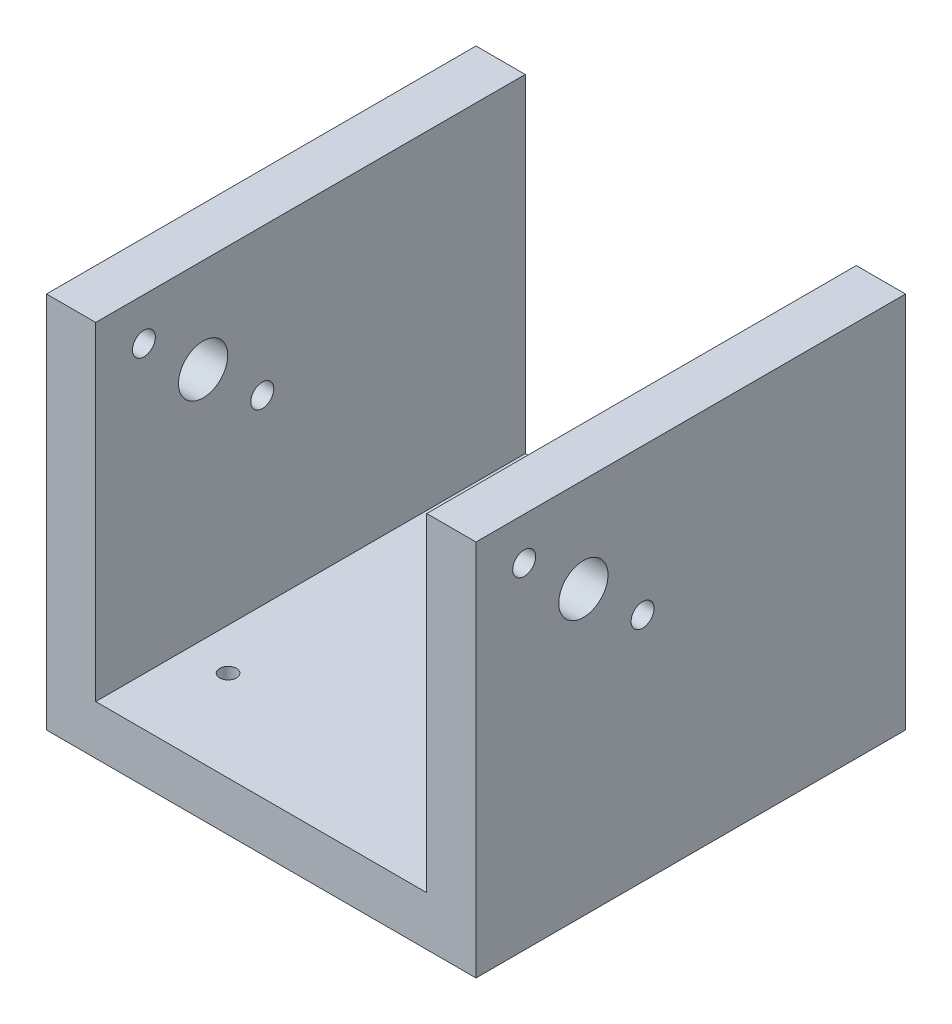
SolidWorks part; units mm, degrees
ref_plane "Front Plane" through (0, 0, 0) normal (0, 0, 1) x (1, 0, 0)
ref_plane "Top Plane" through (0, 0, 0) normal (0, 1, 0) x (1, 0, 0)
ref_plane "Right Plane" through (0, 0, 0) normal (1, 0, 0) x (0, 0, -1)
sketch "Sketch1" plane through (0, 0, 0) normal (0, 1, 0) x (1, 0, 0)
  line L0 (-65.4074, 35.4074) -> (-65.4074, 65.4074)
  line L1 (-37.7595, 37.7595) -> (37.7595, 37.7595) construction
  line L2 (-37.7595, 37.7595) -> (-37.7595, -37.7595) construction
  line L3 (-37.7595, -37.7595) -> (37.7595, -37.7595) construction
  line L4 (37.7595, 37.7595) -> (37.7595, -37.7595) construction
  line L5 (-37.7595, 37.7595) -> (37.7595, -37.7595) construction
  line L6 (-37.7595, -37.7595) -> (37.7595, 37.7595) construction
  line L7 (-35.4074, 65.4074) -> (35.4074, 65.4074)
  line L8 (-65.4074, 35.4074) -> (-65.4074, -35.4074)
  line L9 (-35.4074, -65.4074) -> (35.4074, -65.4074)
  line L10 (65.4074, 35.4074) -> (65.4074, -35.4074)
  line L11 (-65.4074, 65.4074) -> (65.4074, -65.4074) construction
  line L12 (-65.4074, -65.4074) -> (65.4074, 65.4074) construction
  line L13 (-65.4074, 65.4074) -> (-35.4074, 65.4074)
  line L14 (35.4074, 65.4074) -> (65.4074, 65.4074)
  line L15 (65.4074, 65.4074) -> (65.4074, 35.4074)
  line L16 (65.4074, -35.4074) -> (65.4074, -65.4074)
  line L17 (65.4074, -65.4074) -> (35.4074, -65.4074)
  line L18 (-65.4074, -35.4074) -> (-65.4074, -65.4074)
  line L19 (-65.4074, -65.4074) -> (-35.4074, -65.4074)
  circle A0 centre (37.7595, 37.7595) radius 2.55
  circle A1 centre (37.7595, -37.7595) radius 2.55
  circle A2 centre (-37.7595, -37.7595) radius 2.55
  circle A3 centre (-37.7595, 37.7595) radius 2.55
  arc A5 (-35.4074, -65.4074) -> (-65.4074, -35.4074) centre (-35.4074, -35.4074) cw construction
  arc A6 (-35.4074, 65.4074) -> (-65.4074, 35.4074) centre (-35.4074, 35.4074) ccw construction
  arc A7 (35.4074, 65.4074) -> (65.4074, 35.4074) centre (35.4074, 35.4074) cw construction
  arc A8 (65.4074, -35.4074) -> (35.4074, -65.4074) centre (35.4074, -35.4074) cw construction
  point P0 (0, 0)
  point P6 (0, 0)
  point P21 (0, 0)
  dimension "D3" = 5.1
  dimension "D5" = 30
  dimension "D1" = 106.8
  dimension "D2" = 185
  dimension "D4" = 4
extrude "Boss-Extrude1" add sketch "Sketch1" along normal blind 15
sketch "Sketch2" plane through (0, 15, 0) normal (0, 1, 0) x (1, 0, 0)
  line L4 (-65.4074, -65.4074) -> (65.4074, -65.4074)
  line L5 (65.4074, -65.4074) -> (65.4074, 65.4074)
  line L6 (65.4074, 65.4074) -> (-65.4074, 65.4074)
  line L7 (-65.4074, 65.4074) -> (-65.4074, -65.4074)
  line L9 (65.4074, -65.4074) -> (65.4074, 65.4074)
  line L11 (-65.4074, 65.4074) -> (-65.4074, -65.4074)
  line L21 (-50.4074, 50.4074) -> (-50.4074, -50.4074)
  line L23 (50.4074, -50.4074) -> (50.4074, 50.4074)
  line L24 (-65.4074, -65.4074) -> (65.4074, -65.4074)
  line L25 (65.4074, -65.4074) -> (65.4074, 65.4074)
  line L26 (65.4074, 65.4074) -> (-65.4074, 65.4074)
  line L27 (-65.4074, 65.4074) -> (-65.4074, -65.4074)
  line L28 (-65.4074, -65.4074) -> (-50.4074, -65.4074)
  line L29 (65.4074, -65.4074) -> (65.4074, 65.4074)
  line L30 (65.4074, 65.4074) -> (50.4074, 65.4074)
  line L31 (-65.4074, 65.4074) -> (-65.4074, -65.4074)
  line L32 (50.4074, 50.4074) -> (50.4074, 65.4074)
  line L33 (50.4074, -50.4074) -> (50.4074, -65.4074)
  line L34 (-50.4074, -50.4074) -> (-50.4074, -65.4074)
  line L35 (-50.4074, 50.4074) -> (-50.4074, 65.4074)
  line L36 (-50.4074, 65.4074) -> (-65.4074, 65.4074)
  line L37 (65.4074, 65.4074) -> (-65.4074, 65.4074) construction
  line L38 (50.4074, 50.4074) -> (-50.4074, 50.4074) construction
  line L39 (-50.4074, -50.4074) -> (50.4074, -50.4074) construction
  line L40 (50.4074, -65.4074) -> (65.4074, -65.4074)
  line L41 (-65.4074, -65.4074) -> (65.4074, -65.4074) construction
  line M18 (-65.4074, -65.4074) -> (65.4074, -65.4074)
  line M20 (65.4074, -65.4074) -> (65.4074, 65.4074)
  line M22 (65.4074, 65.4074) -> (-65.4074, 65.4074)
  line M24 (-65.4074, 65.4074) -> (-65.4074, -65.4074)
  dimension "D1" = 0
  dimension "D2" = 0
  dimension "D3" = 15
extrude "Boss-Extrude2" add sketch "Sketch2" along normal blind 100 contours L23 L33 L32 M18 M20 M22 | L21 L35 L34 M22 M24 M18
sketch "Sketch3" plane through (-65.4074, 0, 0) normal (-1, 0, 0) x (0, 0, 1)
  line L0 (65.4074, 115) -> (-65.4074, 0) construction
  line L1 (0, 57.5) -> (0, 0) construction
  line L2 (0, 57.5) -> (0, 115) construction
  line L3 (0, 57.5) -> (65.4074, 57.5) construction
  line L4 (-65.4074, 0) -> (65.4074, 0)
  line L5 (65.4074, 0) -> (65.4074, 115)
  line L6 (65.4074, 115) -> (-65.4074, 115)
  line L7 (-65.4074, 115) -> (-65.4074, 0)
  line L8 (-65.4074, 0) -> (65.4074, 0) construction
  line L9 (65.4074, 0) -> (65.4074, 115) construction
  line L10 (65.4074, 115) -> (-65.4074, 115) construction
  line L11 (-65.4074, 115) -> (-65.4074, 0) construction
  line L12 (0, 115) -> (65.4074, 57.5) construction
  line L13 (14.6786, 70.404) -> (50.7288, 102.096) construction
  circle A0 centre (32.7037, 86.25) radius 7.5
  circle A1 centre (14.6786, 70.404) radius 3.5
  circle A2 centre (50.7288, 102.096) radius 3.5
  point P13 (32.7037, 86.25)
  dimension "D2" = 15
  dimension "D4" = 7
  dimension "D5" = 7
  dimension "D3" = 48
  dimension "D1" = 0
extrude "Cut-Extrude1" cut sketch "Sketch3" against normal up to surface (130.8148 mm away) up to face at (65.4074, 57.5, 0)
